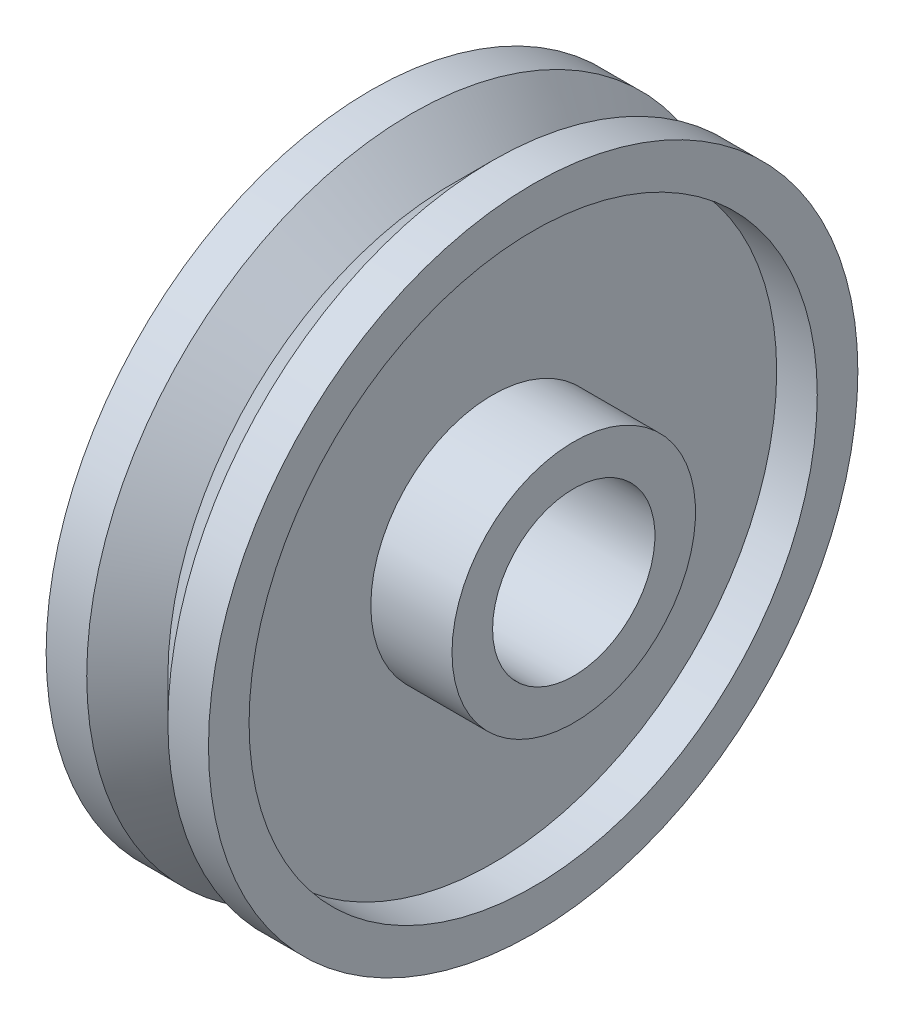
SolidWorks part; units mm, degrees
material "Copper-Cobalt-Beryllium alloy, UNS C17500"
ref_plane "Front Plane" through (0, 0, 0) normal (0, 0, 1) x (1, 0, 0)
ref_plane "Top Plane" through (0, 0, 0) normal (0, 1, 0) x (1, 0, 0)
ref_plane "Right Plane" through (0, 0, 0) normal (1, 0, 0) x (0, 0, -1)
sketch "Sketch1" plane through (0, 0, 0) normal (0, 0, 1) x (1, 0, 0)
  line L0 (0, 66.2428) -> (0, -36.2002) construction
  line L1 (-36.1951, 0) -> (41.2178, 0) construction
  line L2 (0, 12.7) -> (0, 44.45)
  line L3 (0, 44.45) -> (6.35, 50.8)
  line L4 (6.35, 50.8) -> (12.7, 50.8)
  line L5 (12.7, 50.8) -> (12.7, 44.45)
  line L6 (12.7, 44.45) -> (6.35, 44.45)
  line L7 (6.35, 44.45) -> (6.35, 19.05)
  line L8 (6.35, 19.05) -> (19.05, 19.05)
  line L9 (19.05, 19.05) -> (19.05, 12.7)
  line L10 (19.05, 12.7) -> (-19.05, 12.7)
  line L11 (-6.35, 19.05) -> (-19.05, 19.05)
  line L12 (0, 44.45) -> (-6.35, 50.8)
  line L13 (-6.35, 50.8) -> (-12.7, 50.8)
  line L14 (-12.7, 50.8) -> (-12.7, 44.45)
  line L15 (-12.7, 44.45) -> (-6.35, 44.45)
  line L16 (-6.35, 44.45) -> (-6.35, 19.05)
  line L17 (-19.05, 19.05) -> (-19.05, 12.7)
  line L18 (0, 44.45) -> (-6.35, 50.8)
  point P21 (0, -36.2002)
  point P22 (54.0164, 0)
  point P23 (-49.3965, 0)
  point P24 (41.2178, 0)
  point P25 (-36.1951, 0)
  dimension "D1" = 45
  dimension "D2" = 6.35
  dimension "D3" = 6.35
  dimension "D4" = 19.05
  dimension "D5" = 12.7
  dimension "D6" = 19.05
  dimension "D7" = 44.45
  dimension "D8" = 50.8
revolve "Revolve1" add sketch "Sketch1" angle 360 about L1
